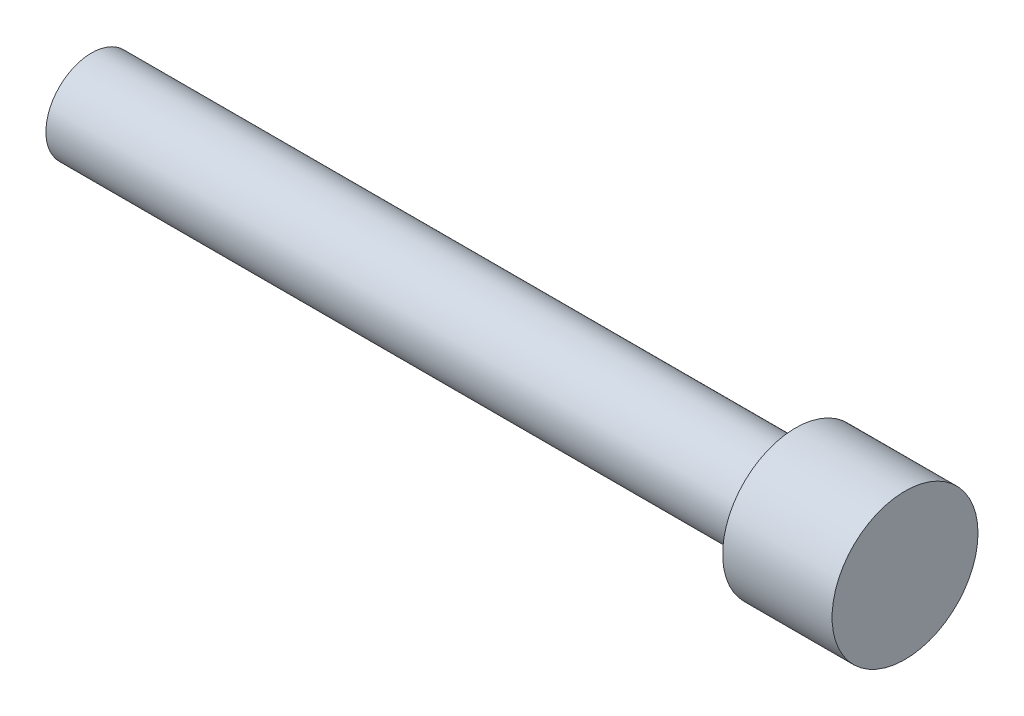
SolidWorks part; units mm, degrees
ref_plane "Front Plane" through (0, 0, 0) normal (0, 0, 1) x (1, 0, 0)
ref_plane "Top Plane" through (0, 0, 0) normal (0, 1, 0) x (1, 0, 0)
ref_plane "Right Plane" through (0, 0, 0) normal (1, 0, 0) x (0, 0, -1)
sketch "Sketch1" plane through (0, 0, 0) normal (1, 0, 0) x (0, 0, -1)
  circle A0 centre (0, 0) radius 1.25
  dimension "D1" = 2.5
extrude "Boss-Extrude1" add sketch "Sketch1" along normal mid plane 19.3
sketch "Sketch2" plane through (9.65, 0, 0) normal (1, 0, 0) x (0, 0, -1)
  circle A0 centre (0, 0) radius 2
  dimension "D1" = 4
extrude "Boss-Extrude2" add sketch "Sketch2" along normal blind 3
